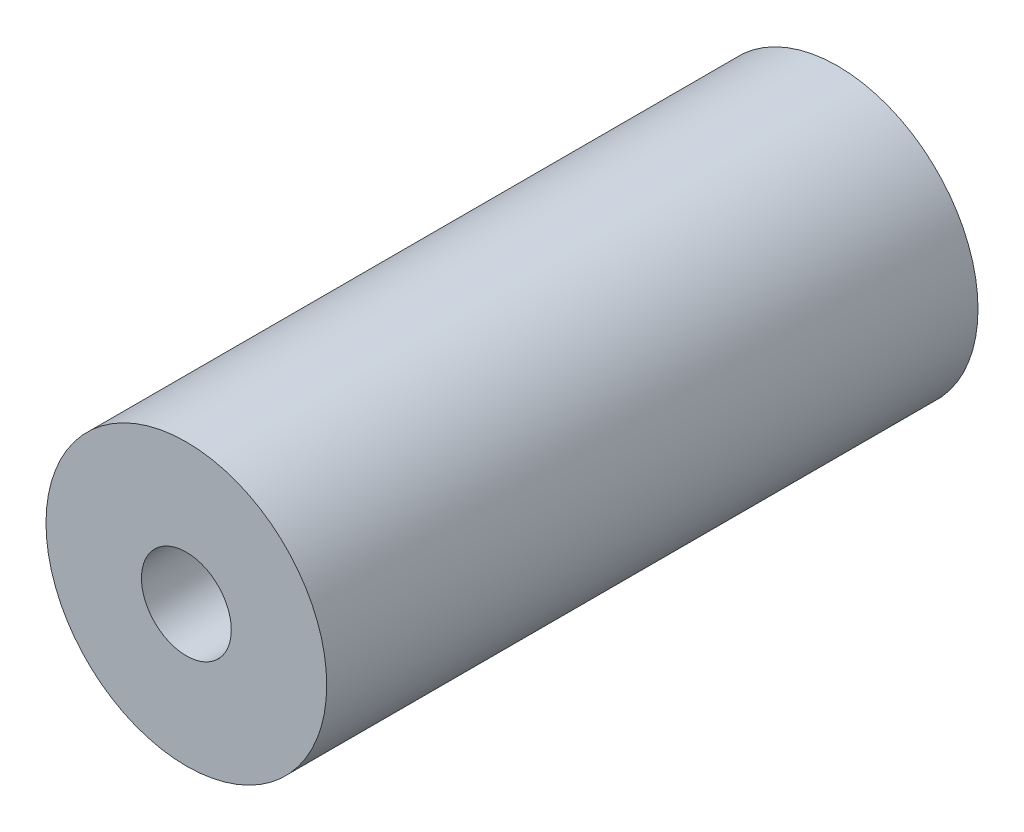
SolidWorks part; units mm, degrees
ref_plane "Alzado" through (0, 0, 0) normal (0, 0, 1) x (1, 0, 0)
ref_plane "Planta" through (0, 0, 0) normal (0, 1, 0) x (1, 0, 0)
ref_plane "Vista lateral" through (0, 0, 0) normal (1, 0, 0) x (0, 0, -1)
sketch "Croquis1" plane through (0, 0, 0) normal (0, 0, 1) x (1, 0, 0)
  circle A0 centre (0, 0) radius 12.5
  dimension "D1" = 25
extrude "Saliente-Extruir1" add sketch "Croquis1" against normal mid plane 58
sketch "Croquis2" plane through (0, 0, 29) normal (0, 0, 1) x (1, 0, 0)
  circle A0 centre (0, 0) radius 4
  dimension "D1" = 8
extrude "Cortar-Extruir1" cut sketch "Croquis2" against normal blind 70
